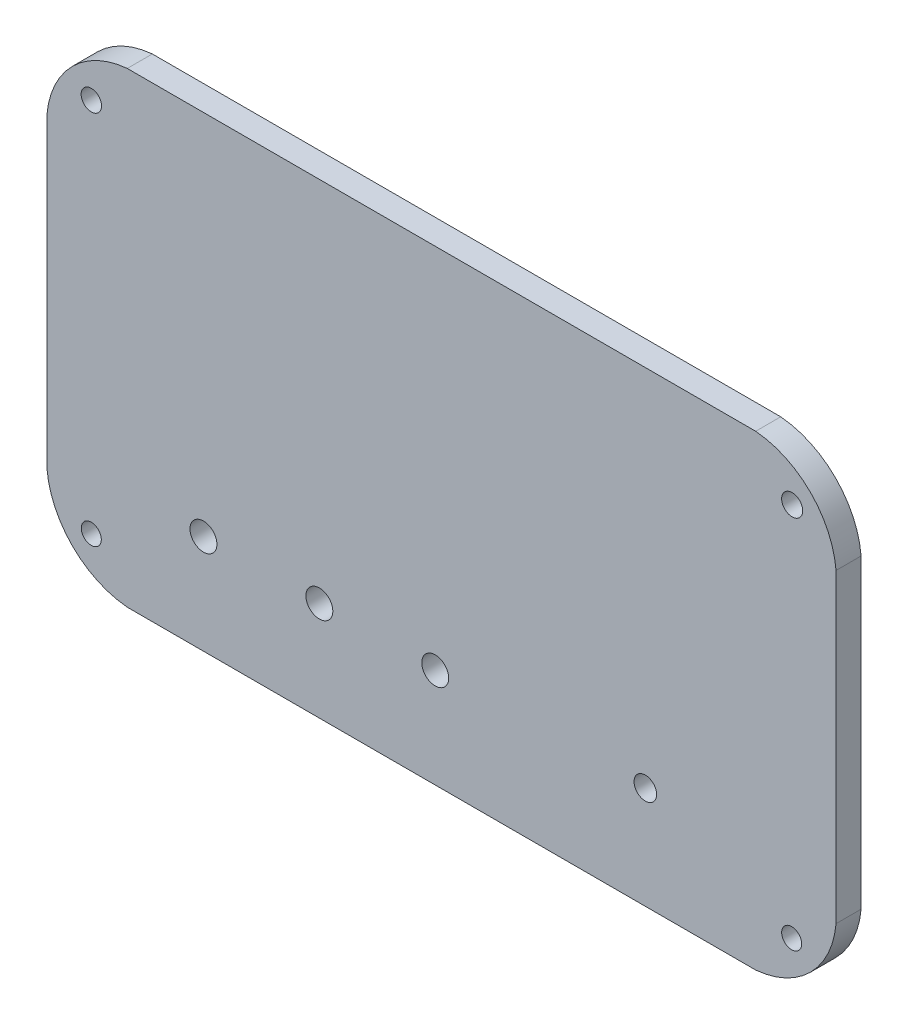
SolidWorks part; units mm, degrees
ref_plane "Спереди" through (0, 0, 0) normal (0, 0, 1) x (1, 0, 0)
ref_plane "Сверху" through (0, 0, 0) normal (0, 1, 0) x (1, 0, 0)
ref_plane "Справа" through (0, 0, 0) normal (1, 0, 0) x (0, 0, -1)
sketch "Эскиз1" plane through (0, 0, 0) normal (0, 0, 1) x (1, 0, 0)
  line L1 (-63, 1.4541) -> (63, 1.4541) construction
  line L3 (63, -22.9658) -> (63, 25.8739)
  line L4 (50.1698, 38.7041) -> (-50.1698, 38.7041)
  line L5 (-63, 25.8739) -> (-63, -22.9658)
  line L6 (-50.1698, -35.7959) -> (50.1698, -35.7959)
  arc A0 (-50.1698, 38.7041) -> (-63, 25.8739) centre (-48.9505, 24.6545) ccw
  arc A1 (50.1698, 38.7041) -> (63, 25.8739) centre (48.9505, 24.6545) cw
  arc A2 (50.1698, -35.7959) -> (63, -22.9658) centre (48.9505, -21.7464) ccw
  arc A3 (-50.1698, -35.7959) -> (-63, -22.9658) centre (-48.9505, -21.7464) cw
  point P14 (0, 1.4541)
extrude "Бобышка-Вытянуть1" add sketch "Эскиз1" along normal blind 4
sketch "Эскиз2" plane through (0, 0, 4) normal (0, 0, 1) x (1, 0, 0)
  line L0 (-38, -17.7959) -> (-19.5, -17.7959) construction
  line L3 (-19.5, -17.7959) -> (-1, -17.7959) construction
  line L4 (-1, -17.7959) -> (63, -17.7959) construction
  line L5 (63, -22.9658) -> (63, 25.8739) construction
  line L6 (-38, -17.7959) -> (-38, -35.7959) construction
  line L7 (-50.1698, -35.7959) -> (50.1698, -35.7959) construction
  circle A0 centre (-38, -19.9459) radius 2.15
  circle A3 centre (32.5542, -19.4425) radius 1.8
  circle A4 centre (-19.5, -19.9459) radius 2.15
  circle A5 centre (-1, -19.9459) radius 2.15
  dimension "D1" = 4.3
  dimension "D3" = 3.6
  dimension "D4" = 18
  dimension "D5" = 64
  dimension "D2" = 3
extrude "Вырез-Вытянуть1" cut sketch "Эскиз2" against normal blind 4
sketch "Эскиз3" plane through (0, 0, 0) normal (0, 0, -1) x (-1, 0, 0)
  circle A0 centre (-55.9916, 31.4552) radius 1.6824
  circle A1 centre (55.9052, 31.4552) radius 1.6318
  circle A2 centre (-55.915, -28.5168) radius 1.6
  circle A3 centre (55.915, -28.5168) radius 1.6
extrude "Вырез-Вытянуть2" cut sketch "Эскиз3" against normal blind 4
